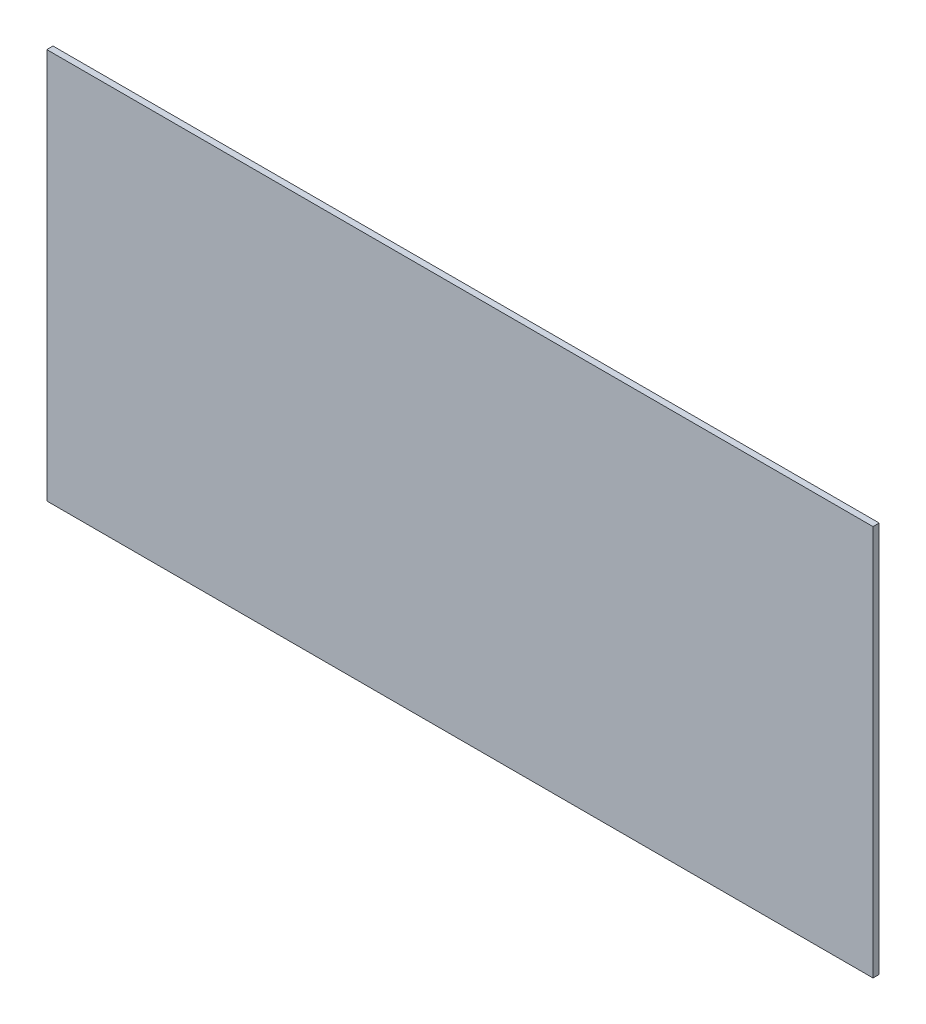
SolidWorks part; units mm, degrees
ref_plane "Front Plane" through (0, 0, 0) normal (0, 0, 1) x (1, 0, 0)
ref_plane "Top Plane" through (0, 0, 0) normal (0, 1, 0) x (1, 0, 0)
ref_plane "Right Plane" through (0, 0, 0) normal (1, 0, 0) x (0, 0, -1)
sketch "Sketch1" plane through (0, 0, 0) normal (0, 0, 1) x (1, 0, 0)
  line L1 (211.35, -100) -> (-211.35, -100)
  line L2 (211.35, -100) -> (211.35, 100)
  line L3 (211.35, 100) -> (-211.35, 100)
  line L4 (-211.35, -100) -> (-211.35, 100)
  line L5 (211.35, -100) -> (-211.35, 100) construction
  line L6 (211.35, 100) -> (-211.35, -100) construction
  point P0 (0, 0)
  dimension "D1" = 422.7
  dimension "D2" = 200
extrude "Boss-Extrude2" add sketch "Sketch1" along normal blind 3.175
